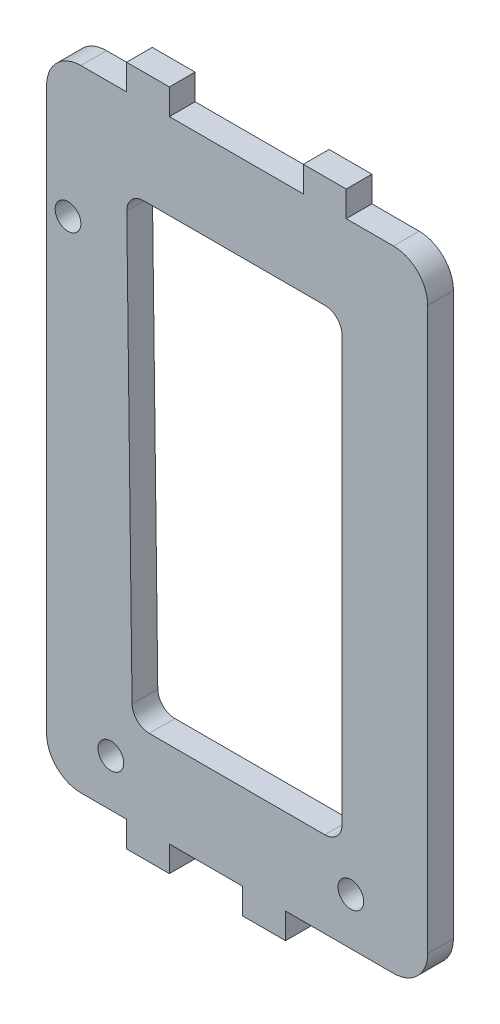
SolidWorks part; units mm, degrees
ref_plane "Alzado" through (0, 0, 0) normal (0, 0, 1) x (1, 0, 0)
ref_plane "Planta" through (0, 0, 0) normal (0, 1, 0) x (1, 0, 0)
ref_plane "Vista lateral" through (0, 0, 0) normal (1, 0, 0) x (0, 0, -1)
sketch "Croquis1" plane through (0, 0, 0) normal (0, 0, 1) x (1, 0, 0)
  line L0 (-27.7352, 52.6459) -> (-43.3652, 52.6459)
  line L1 (-48.3652, -20.8541) -> (-48.3652, -23.8541)
  line L2 (-48.3652, -23.8541) -> (-43.3652, -23.8541)
  line L3 (-43.3652, -23.8541) -> (-43.3652, -20.8541)
  line L4 (-34.8152, -23.8541) -> (-34.8152, -20.8541)
  line L5 (-34.8152, -20.8541) -> (-43.3652, -20.8541)
  line L6 (-57.6952, 48.6459) -> (-57.6952, -16.8541)
  line L8 (-34.8152, -23.8541) -> (-29.8152, -23.8541)
  line L9 (-29.8152, -23.8541) -> (-29.8152, -20.8541)
  line L10 (-29.8152, -20.8541) -> (-17.2252, -20.8541)
  line L12 (-27.7352, 55.6459) -> (-22.7352, 55.6459)
  line L13 (-48.3652, -20.8541) -> (-53.6952, -20.8541)
  line L14 (-13.2252, 48.6459) -> (-13.2252, -16.8541)
  line L16 (-22.7352, 55.6459) -> (-22.7352, 52.6459)
  line L17 (-27.7352, 55.6459) -> (-27.7352, 52.6459)
  line L18 (-22.7352, 52.6459) -> (-17.2252, 52.6459)
  line L20 (-35.5502, 42.6459) -> (-25.2252, 42.6459)
  line L21 (-23.2252, 40.6459) -> (-23.2252, -8.8541)
  line L22 (-25.2252, -10.8541) -> (-45.7201, -10.8541)
  line L23 (-47.7199, -8.8792) -> (-48.3399, 40.6208)
  line L24 (-46.34, 42.6459) -> (-35.5502, 42.6459)
  line L27 (-53.6952, 52.6459) -> (-48.3652, 52.6459)
  line L28 (-48.3652, 52.6459) -> (-48.3652, 55.6459)
  line L29 (-48.3652, 55.6459) -> (-43.3652, 55.6459)
  line L30 (-43.3652, 55.6459) -> (-43.3652, 52.6459)
  arc A0 (-53.6952, -20.8541) -> (-57.6952, -16.8541) centre (-53.6952, -16.8541) cw
  arc A1 (-13.2252, -16.8541) -> (-17.2252, -20.8541) centre (-17.2252, -16.8541) cw
  arc A2 (-17.2252, 52.6459) -> (-13.2252, 48.6459) centre (-17.2252, 48.6459) cw
  arc A3 (-57.6952, 48.6459) -> (-53.6952, 52.6459) centre (-53.6952, 48.6459) cw
  arc A4 (-23.2252, -8.8541) -> (-25.2252, -10.8541) centre (-25.2252, -8.8541) cw
  arc A5 (-25.2252, 42.6459) -> (-23.2252, 40.6459) centre (-25.2252, 40.6459) cw
  arc A6 (-48.3399, 40.6208) -> (-46.34, 42.6459) centre (-46.34, 40.6459) cw
  arc A7 (-45.7201, -10.8541) -> (-47.7199, -8.8792) centre (-45.7201, -8.8541) cw
  circle A8 centre (-55.1952, 36.6459) radius 1.5
  circle A9 centre (-50.1952, -15.3541) radius 1.5
  circle A10 centre (-22.1952, -15.3541) radius 1.5
  point P47 (-8.5252, 49.1459)
  dimension "D1" = 4
  dimension "D2" = 2
extrude "Saliente-Extruir1" add sketch "Croquis1" along normal blind 3
